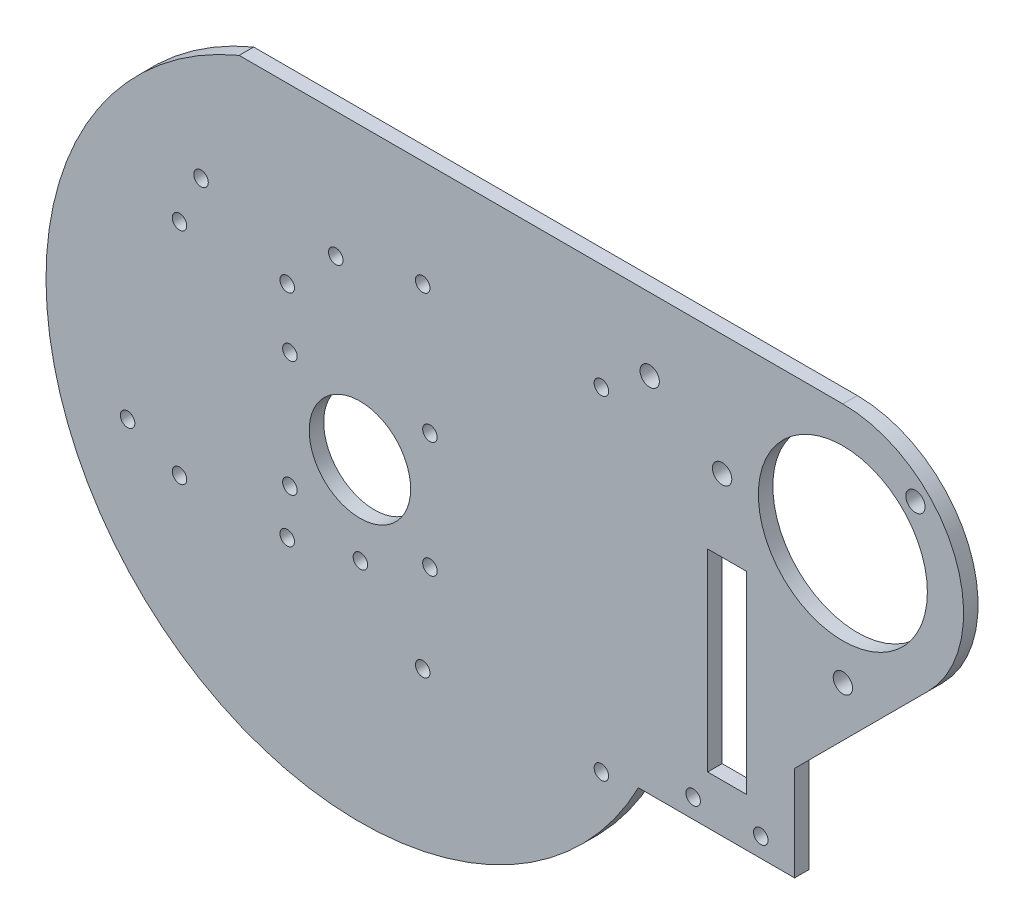
SolidWorks part; units mm, degrees
ref_plane "前视基准面" through (0, 0, 0) normal (0, 0, 1) x (1, 0, 0)
ref_plane "上视基准面" through (0, 0, 0) normal (0, 1, 0) x (1, 0, 0)
ref_plane "右视基准面" through (0, 0, 0) normal (1, 0, 0) x (0, 0, -1)
sketch "Sketch1" plane through (0, 0, 0) normal (0, 0, 1) x (1, 0, 0)
  line L0 (-10.9179, 60) -> (113.3582, 60) construction
  line L3 (-33.1662, 50) -> (-60, 50)
  line L4 (-60, 0) -> (-60, 50)
  line L6 (67.51, -32.8453) -> (81.2655, -19.0899) construction
  line L7 (90, -10.3553) -> (117.6777, 17.3223)
  line L12 (76, 7.9315) -> (76, -17.4174) construction
  line L13 (0, 60) -> (100, 60)
  line L15 (72, 20) -> (80, 20)
  line L16 (72, 20) -> (72, -20)
  line L17 (72, -20) -> (80, -20)
  line L18 (80, 20) -> (80, -20)
  line L19 (72, 20) -> (80, -20) construction
  line L20 (72, -20) -> (80, 20) construction
  line L23 (90, -30) -> (56.5685, -30)
  line L24 (90, -30) -> (90, -10.3553)
  line L25 (56.5685, -30) -> (51.9615, -30)
  line L26 (57.5608, -26) -> (84.9155, -26) construction
  arc A0 (0, 60) -> (51.9615, -30) centre (0, 0) ccw
  circle A2 centre (0, 0) radius 10.5
  arc A8 (117.6777, 17.3223) -> (100, 60) centre (100, 35) ccw
  circle A9 centre (100, 35) radius 17.5
  circle A10 centre (69, -26) radius 1.5
  circle A11 centre (83, -26) radius 1.5
  point P18 (76, 0)
  dimension "D1" = 120
  dimension "D2" = 136
  dimension "D3" = 21
  dimension "D5" = 50
  dimension "D4" = 100
  dimension "D6" = 35
  dimension "D13" = 7
  dimension "D7" = 10
  dimension "D8" = 8
  dimension "D9" = 40
  dimension "D10" = 90
  dimension "D11" = 150
  dimension "D12" = 6
extrude "Boss-Extrude1" add sketch "Sketch1" along normal blind 3
sketch "Sketch2" plane through (0, 0, 3) normal (0, 0, 1) x (1, 0, 0)
  line L1 (-60, 0) -> (-60, 50) construction
  line L2 (0, 60) -> (100, 60) construction
  circle A1 centre (0, 0) radius 57
  circle A2 centre (60, 45) radius 2
  circle A6 centre (100, 35) radius 14
  dimension "D1" = 15
  dimension "D5" = 28
  dimension "D2" = 120
extrude "Cut-Extrude1" cut sketch "Sketch2" against normal up to next
sketch "Sketch3" plane through (0, 0, 3) normal (0, 0, 1) x (1, 0, 0)
  line L0 (117.6777, 52.6777) -> (112.3744, 47.3744) construction
  circle A0 centre (100, 35) radius 17.5 construction
  circle A1 centre (100, 35) radius 25 construction
  circle A2 centre (100, 10) radius 2
  circle A3 centre (75, 35) radius 2
  circle A4 centre (115.026, 50.026) radius 2
  dimension "D1" = 35
extrude "Cut-Extrude2" cut sketch "Sketch3" against normal up to next
sketch "Sketch4" plane through (0, 0, 3) normal (0, 0, 1) x (1, 0, 0)
  circle A0 centre (0, 0) radius 60
  circle A1 centre (0, 0) radius 65
extrude "Boss-Extrude2" add sketch "Sketch4" against normal up to surface (3 mm away) up to face at (102, 10, 0)
sketch "Sketch5" plane through (0, 0, 3) normal (0, 0, 1) x (1, 0, 0)
  line L1 (-60, 50) -> (-41.5331, 50)
  line L2 (-60, 50) -> (-60, 25)
  arc A0 (-41.5331, 50) -> (-60, 25) centre (0, 0) ccw
extrude "Cut-Extrude3" cut sketch "Sketch5" against normal blind 10
sketch "Sketch6" plane through (0, 0, 3) normal (0, 0, 1) x (1, 0, 0)
  line L0 (25, 60) -> (-25, 60)
  arc A0 (25, 60) -> (57.6628, -30) centre (0, 0) ccw construction
  arc A1 (-25, 60) -> (25, 60) centre (0, 0) cw
extrude "Cut-Extrude4" cut sketch "Sketch6" against normal blind 10
sketch "Sketch7" plane through (0, 0, 3) normal (0, 0, 1) x (1, 0, 0)
  circle A0 centre (-14.5, 12) radius 1.5
  circle A1 centre (14.5, 12) radius 1.5
  circle A2 centre (-14.5, -12) radius 1.5
  circle A3 centre (14.5, -12) radius 1.5
extrude "Cut-Extrude5" cut sketch "Sketch7" against normal up to next
sketch "Sketch8" plane through (0, 0, 3) normal (0, 0, 1) x (1, 0, 0)
  line L0 (-25, 60) -> (100, 60) construction
  line L1 (90, -30) -> (90, -10.3553) construction
  circle A0 centre (50, 38) radius 1.5
  circle A1 centre (13, 38) radius 1.5
  circle A2 centre (50, -31) radius 1.5
  circle A3 centre (13, -31) radius 1.5
  circle A4 centre (-5, 34) radius 1.5
  circle A6 centre (-32.9, 34) radius 1.5
  circle A7 centre (0.1, -18.1) radius 1.5
  circle A8 centre (-48.1, -16.8) radius 1.5
  dimension "D1" = 22
  dimension "D2" = 40
  dimension "D3" = 37
  dimension "D4" = 69
  dimension "D6" = 26
  dimension "D8" = 27.9
  dimension "D9" = 5.1
  dimension "D11" = 15.2
  dimension "D12" = 1.3
  dimension "D5" = 69
  dimension "D7" = 95
  dimension "D10" = 50.8
extrude "Cut-Extrude6" cut sketch "Sketch8" against normal up to next
sketch "Sketch9" plane through (0, 0, 3) normal (0, 0, 1) x (1, 0, 0)
  line L0 (-25, 60) -> (100, 60) construction
  circle A4 centre (-15.055, 24) radius 1.5
  circle A5 centre (-15.055, -21.5) radius 1.5
  circle A6 centre (-37.355, 24) radius 1.5
  circle A7 centre (-37.355, -21.5) radius 1.5
  point P10 (0, 0)
  dimension "D1" = 36
  dimension "D2" = 45.5
  dimension "D3" = 22.3
extrude "Cut-Extrude7" cut sketch "Sketch9" against normal up to next
